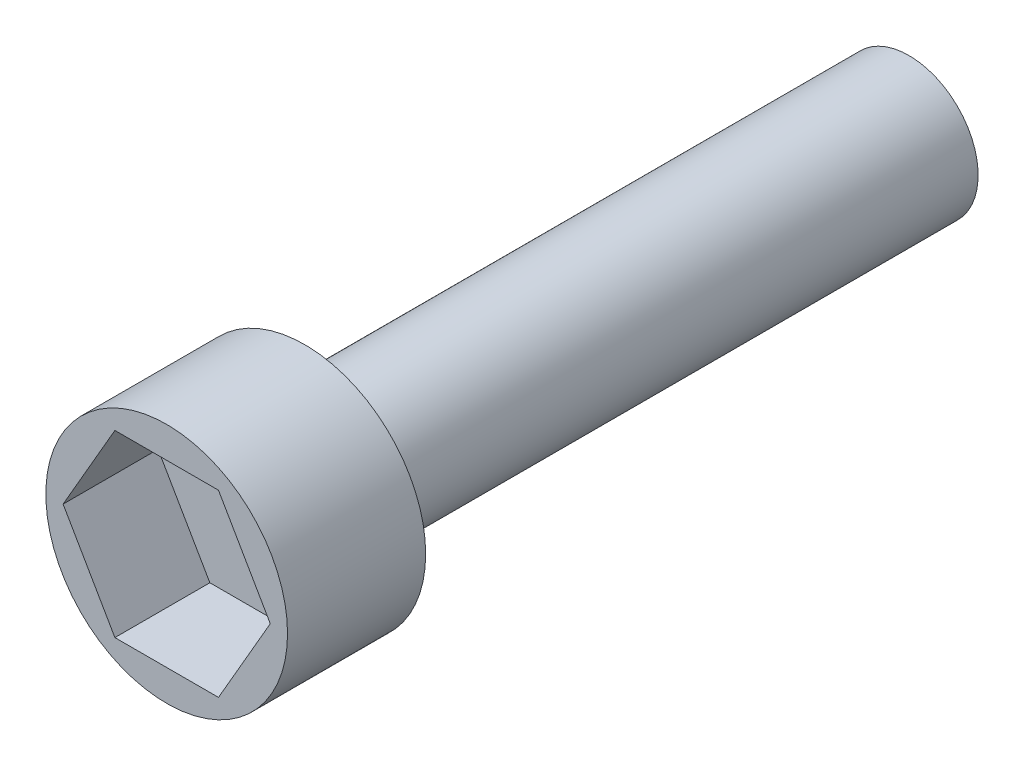
SolidWorks part; units mm, degrees
ref_plane "Front Plane" through (0, 0, 0) normal (0, 0, 1) x (1, 0, 0)
ref_plane "Top Plane" through (0, 0, 0) normal (0, 1, 0) x (1, 0, 0)
ref_plane "Right Plane" through (0, 0, 0) normal (1, 0, 0) x (0, 0, -1)
sketch "Sketch1" plane through (0, 0, 0) normal (0, 1, 0) x (1, 0, 0)
  line L0 (177.8, -889) -> (0, -889)
  line L1 (0, -889) -> (0, -1092.2)
  line L2 (0, -1092.2) -> (177.8, -1092.2)
  line L3 (177.8, -1092.2) -> (177.8, -889)
  line L4 (0, -889) -> (0, -1092.2) construction
revolve "Revolve1" add sketch "Sketch1" angle 360 about L4
sketch "Sketch2" plane through (0, 0, 889) normal (0, 0, -1) x (-1, 0, 0)
  circle A0 centre (0, 0) radius 101.6
extrude "Boss-Extrude1" add sketch "Sketch2" along normal blind 889
sketch "Sketch3" plane through (0, 0, 1092.2) normal (0, 0, 1) x (1, 0, 0)
  line L0 (-152.4, 0) -> (-76.2, -131.9823)
  line L1 (-76.2, -131.9823) -> (76.2, -131.9823)
  line L2 (76.2, -131.9823) -> (152.4, 0)
  line L3 (152.4, 0) -> (76.2, 131.9823)
  line L4 (76.2, 131.9823) -> (-76.2, 131.9823)
  line L5 (-76.2, 131.9823) -> (-152.4, 0)
extrude "Cut-Extrude1" cut sketch "Sketch3" against normal blind 139.7
